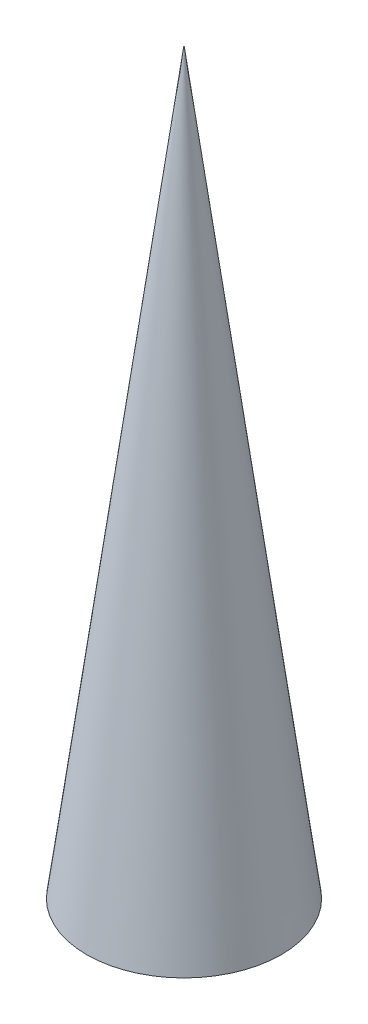
SolidWorks part; units mm, degrees
ref_plane "前视基准面" through (0, 0, 0) normal (0, 0, 1) x (1, 0, 0)
ref_plane "上视基准面" through (0, 0, 0) normal (0, 1, 0) x (1, 0, 0)
ref_plane "右视基准面" through (0, 0, 0) normal (1, 0, 0) x (0, 0, -1)
sketch "草图1" plane through (0, 0, 0) normal (0, 0, 1) x (1, 0, 0)
  line L0 (0, -1.5883) -> (0, -120.8014) construction
  line L1 (0.2091, -1.5883) -> (142.5508, -1082.7806)
  line L2 (-0.2091, -1.5883) -> (-142.5508, -1082.7806)
  line L3 (-142.5508, -1082.7806) -> (142.5508, -1082.7806)
  line L4 (-0.2091, -1.5883) -> (0.2091, -1.5883)
  line L5 (0, -1.5883) -> (0, -1082.7806)
  dimension "D1" = 7.5
revolve "旋转3" add sketch "草图1" angle 360 about L0
